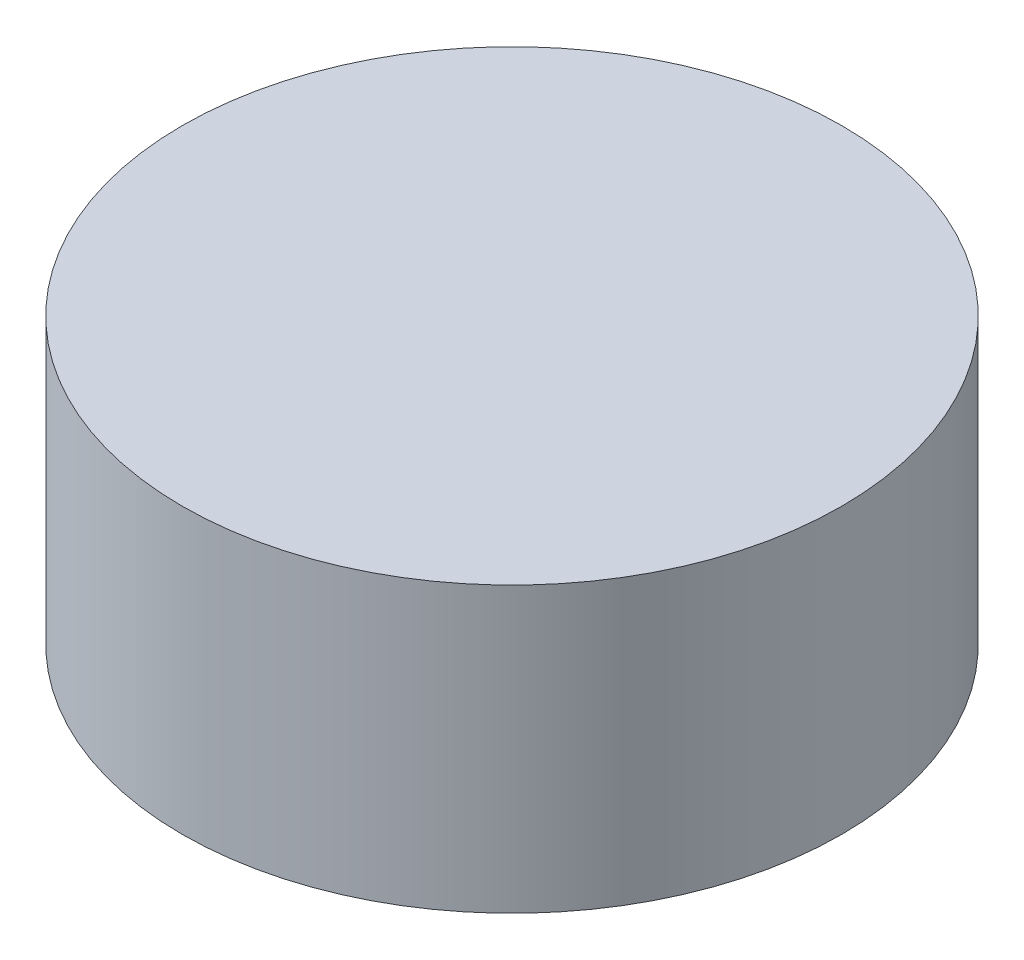
SolidWorks part; units mm, degrees
ref_plane "Front Plane" through (0, 0, 0) normal (0, 0, 1) x (1, 0, 0)
ref_plane "Top Plane" through (0, 0, 0) normal (0, 1, 0) x (1, 0, 0)
ref_plane "Right Plane" through (0, 0, 0) normal (1, 0, 0) x (0, 0, -1)
sketch "Sketch1" plane through (0, 0, 0) normal (0, 1, 0) x (1, 0, 0)
  circle A0 centre (0, 0) radius 29
extrude "Boss-Extrude1" add sketch "Sketch1" along normal blind 25
